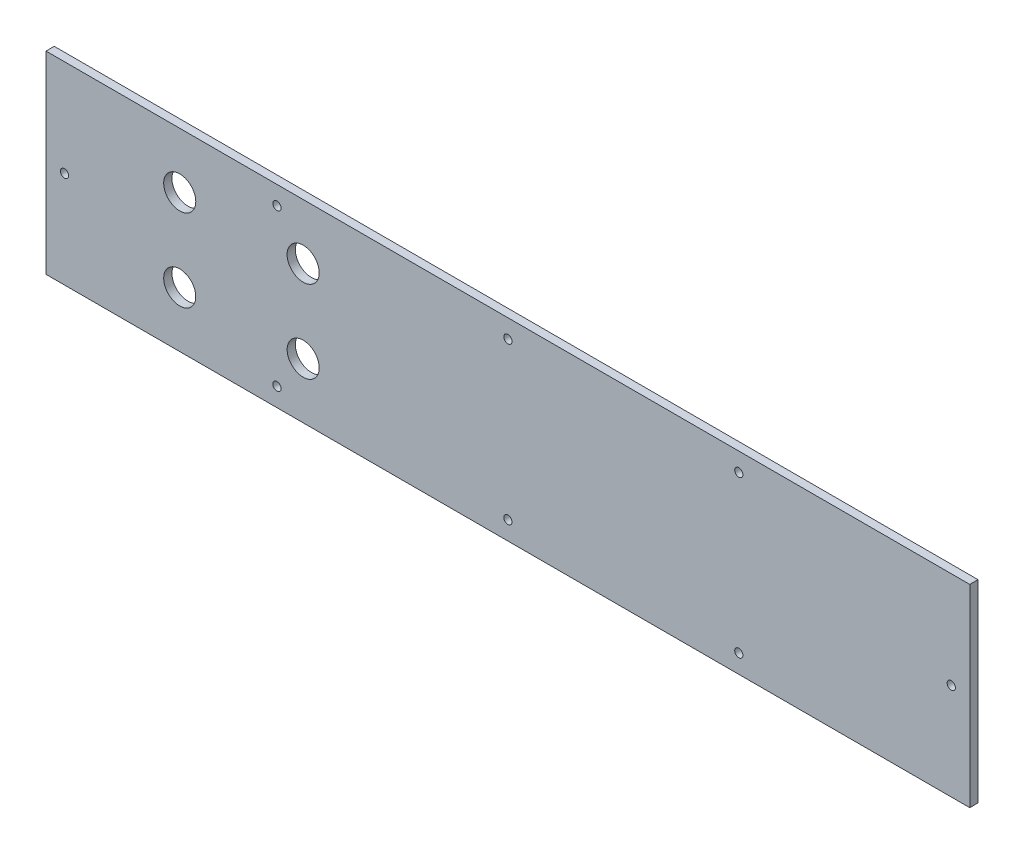
SolidWorks part; units mm, degrees
ref_plane "Piano frontale" through (0, 0, 0) normal (0, 0, 1) x (1, 0, 0)
ref_plane "Piano superiore" through (0, 0, 0) normal (0, 1, 0) x (1, 0, 0)
ref_plane "Piano destro" through (0, 0, 0) normal (1, 0, 0) x (0, 0, -1)
sketch "Schizzo1" plane through (0, 0, 0) normal (0, 0, 1) x (1, 0, 0)
  line L0 (-224.5, 351.6275) -> (-224.5, -66.2585) construction
  line L1 (0, 0) -> (-449, 0)
  line L2 (0, 0) -> (0, 94)
  line L3 (0, 94) -> (-449, 94)
  line L4 (-449, 0) -> (-449, 94)
  line L5 (-384, 47) -> (120.8821, 47) construction
  line L6 (-476.1211, 67) -> (-192.6282, 67) construction
  line L7 (-476.1211, 27) -> (-192.6282, 27) construction
  line L8 (-354, 67) -> (-354, 27) construction
  line L9 (-224.5, 94) -> (-449, 0) construction
  line L10 (-336.75, 47) -> (-336.75, 0) construction
  circle A0 centre (-384, 27) radius 7.8
  circle A1 centre (-9, 47) radius 2
  circle A2 centre (-224.5, 85) radius 2
  circle A3 centre (-440, 47) radius 2
  circle A4 centre (-224.5, 9) radius 2
  circle A5 centre (-324, 27) radius 7.8
  circle A6 centre (-324, 67) radius 7.8
  circle A7 centre (-336.75, 85) radius 2
  circle A8 centre (-384, 67) radius 7.8
  circle A9 centre (-336.75, 9) radius 2
  circle A10 centre (-112.25, 9) radius 2
  circle A11 centre (-112.25, 85) radius 2
  point P9 (-224.5, 47)
  dimension "D3" = 4
  dimension "D2" = 4
  dimension "D5" = 65
  dimension "D8" = 4
  dimension "D9" = 9
  dimension "D12" = 15.6
  dimension "D1" = 449
  dimension "314" = 94
  dimension "D4" = 9
  dimension "D6" = 9
  dimension "D7" = 30
  dimension "D11" = 20
extrude "Estrusione-Estrusione1" add sketch "Schizzo1" along normal blind 4
